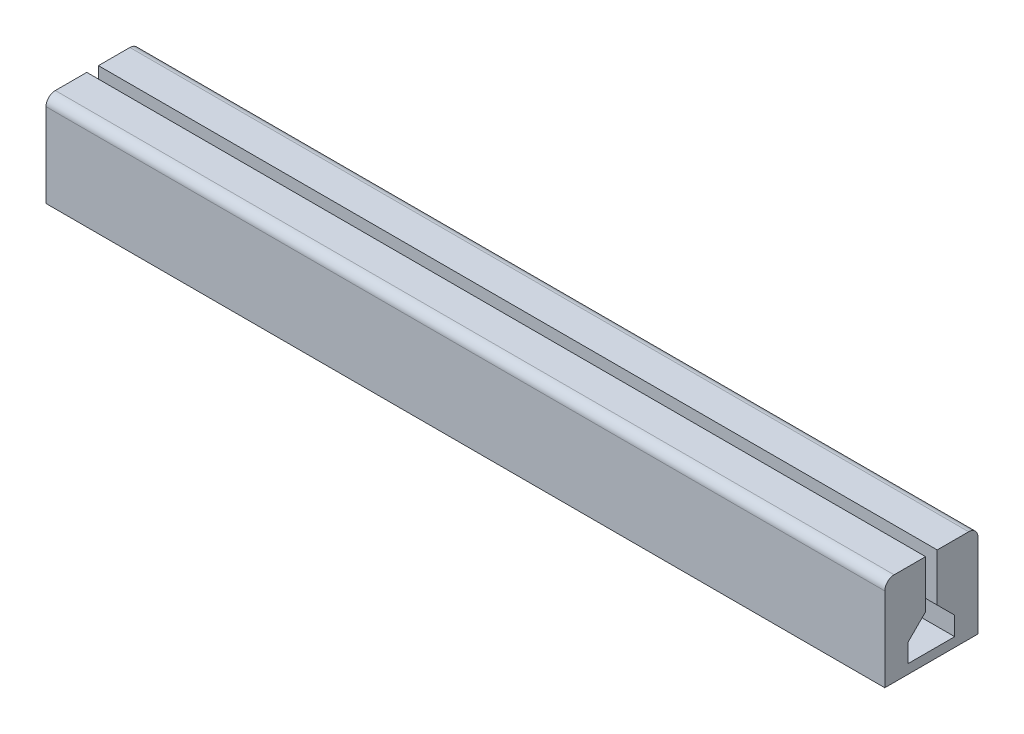
SolidWorks part; units mm, degrees
ref_plane "Front Plane" through (0, 0, 0) normal (0, 0, 1) x (1, 0, 0)
ref_plane "Top Plane" through (0, 0, 0) normal (0, 1, 0) x (1, 0, 0)
ref_plane "Right Plane" through (0, 0, 0) normal (1, 0, 0) x (0, 0, -1)
sketch "Sketch1" plane through (0, 0, 0) normal (1, 0, 0) x (0, 0, -1)
  line L0 (12.7, 0) -> (-12.7, 0)
  line L1 (-12.7, 0) -> (-12.7, 22.86)
  line L2 (-10.16, 25.4) -> (-1.5875, 25.4)
  line L4 (-6.35, 2.54) -> (6.35, 2.54)
  line L5 (0, 2.54) -> (0, 0)
  line L8 (-1.5875, 25.4) -> (-1.5875, 7.62)
  line L9 (-1.5875, 7.62) -> (-6.35, 7.62)
  line L10 (-6.35, 7.62) -> (-6.35, 2.54)
  line L11 (1.5875, 7.62) -> (6.35, 7.62)
  line L12 (1.5875, 25.4) -> (1.5875, 7.62)
  line L15 (10.16, 25.4) -> (1.5875, 25.4)
  line L16 (12.7, 0) -> (12.7, 22.86)
  line L17 (6.35, 7.62) -> (6.35, 2.54)
  line L22 (-8.89, 0) -> (8.89, 0)
  line L30 (-8.89, 10.16) -> (-8.89, 0) construction
  line L31 (10.16, 2.54) -> (-10.16, 2.54) construction
  line L32 (8.89, 10.16) -> (8.89, 0) construction
  line L37 (-4.1275, 22.86) -> (-4.1275, 10.16) construction
  line L38 (-10.16, 22.86) -> (-4.1275, 22.86) construction
  line L39 (-10.16, 2.54) -> (-10.16, 22.86) construction
  line L40 (-4.1275, 10.16) -> (-8.89, 10.16) construction
  line L41 (4.1275, 22.86) -> (4.1275, 10.16) construction
  line L42 (10.16, 2.54) -> (10.16, 22.86) construction
  line L43 (4.1275, 10.16) -> (8.89, 10.16) construction
  line L44 (10.16, 22.86) -> (4.1275, 22.86) construction
  arc A0 (10.16, 25.4) -> (12.7, 22.86) centre (10.16, 22.86) cw
  arc A1 (-12.7, 22.86) -> (-10.16, 25.4) centre (-10.16, 22.86) cw
  arc A2 (-10.16, 22.86) -> (-10.16, 22.86) centre (-10.16, 22.86) cw
  arc A3 (10.16, 22.86) -> (10.16, 22.86) centre (10.16, 22.86) cw
  point P3 (0, 0)
  point P19 (12.7, 25.4)
  point P22 (-12.7, 25.4)
  dimension "D6" = 2.54
  dimension "D1" = 25.4
  dimension "D2" = 5.08
  dimension "D3" = 2.54
  dimension "D4" = 6.35
  dimension "D5" = 1.5875
  dimension "D7" = 2.54
  dimension "D8" = 12.7
extrude "Boss-Extrude1" add sketch "Sketch1" along normal mid plane 228.6 contours L11 L17 L4 L5 L0 L16 L15 L12 | L10 L9 L8 L2 L1 L0 L5 L4
sketch "Sketch2" plane through (0, 0, 0) normal (1, 0, 0) x (0, 0, -1)
  line L5 (-6.35, 7.62) -> (-1.5875, 12.3825)
  line L6 (-1.5875, 25.4) -> (-1.5875, 7.62) construction
  line L7 (-1.5875, 12.3825) -> (-1.5875, 7.62)
  line L8 (-1.5875, 7.62) -> (-6.35, 7.62)
  line L9 (0, 28.4465) -> (0, -4.9749) construction
  line L10 (1.5875, 7.62) -> (6.35, 7.62)
  line L11 (1.5875, 12.3825) -> (1.5875, 7.62)
  line L12 (6.35, 7.62) -> (1.5875, 12.3825)
  point P25 (0, 0)
  dimension "D2" = 45
extrude "Cut-Extrude2" cut sketch "Sketch2" against normal mid plane 228.6
